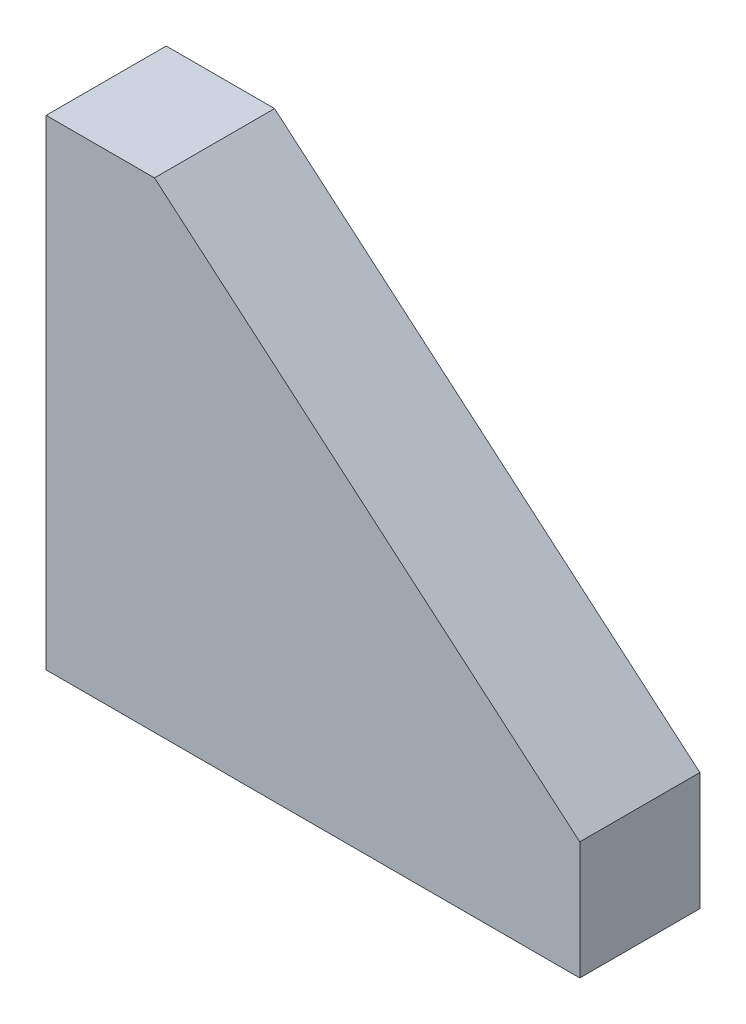
SolidWorks part; units mm, degrees
ref_plane "Front Plane" through (0, 0, 0) normal (0, 0, 1) x (1, 0, 0)
ref_plane "Top Plane" through (0, 0, 0) normal (0, 1, 0) x (1, 0, 0)
ref_plane "Right Plane" through (0, 0, 0) normal (1, 0, 0) x (0, 0, -1)
sketch "Sketch1" plane through (0, 0, 0) normal (0, 0, 1) x (1, 0, 0)
  line L1 (0, 0) -> (25.4, 0)
  line L2 (0, 0) -> (0, 22.86)
  line L3 (0, 22.86) -> (25.4, 22.86)
  line L4 (25.4, 0) -> (25.4, 22.86)
  dimension "D1" = 25.4
  dimension "D2" = 22.86
extrude "Boss-Extrude1" add sketch "Sketch1" along normal blind 5.715
sketch "Sketch2" plane through (0, 0, 5.715) normal (0, 0, 1) x (1, 0, 0)
  line L0 (5.1572, 22.86) -> (25.4, 5.6124)
  line L1 (25.4, 22.86) -> (0, 22.86) construction
  line L2 (25.4, 0) -> (25.4, 22.86) construction
  line L3 (25.4, 5.6124) -> (25.4, 22.86)
  line L4 (25.4, 22.86) -> (5.1572, 22.86)
extrude "Cut-Extrude1" cut sketch "Sketch2" against normal up to next
